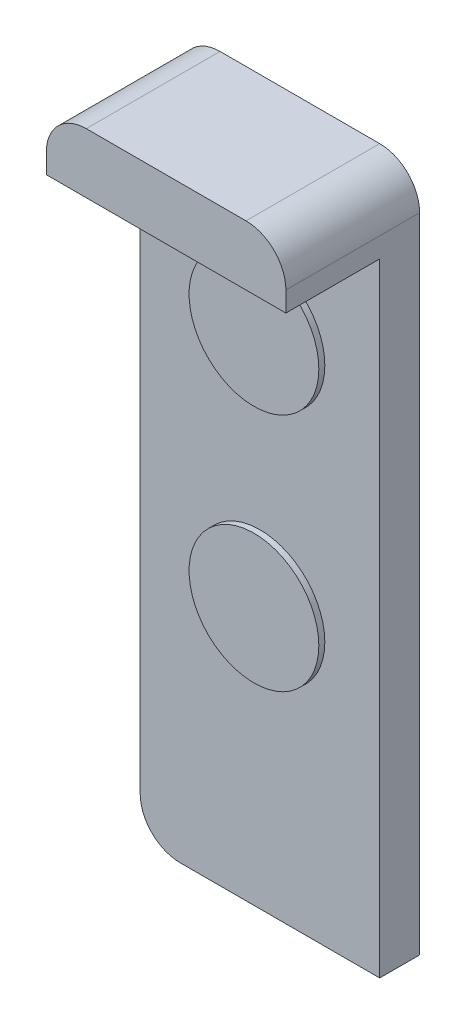
SolidWorks part; units mm, degrees
ref_plane "Plan de face" through (0, 0, 0) normal (0, 0, 1) x (1, 0, 0)
ref_plane "Plan de dessus" through (0, 0, 0) normal (0, 1, 0) x (1, 0, 0)
ref_plane "Plan de droite" through (0, 0, 0) normal (1, 0, 0) x (0, 0, -1)
sketch "Esquisse1" plane through (0, 0, 0) normal (0, 0, 1) x (1, 0, 0)
  line L1 (-3.7662, 20.3915) -> (8.2338, 20.3915)
  line L2 (-3.7662, 20.3915) -> (-3.7662, -13.8085)
  line L3 (-3.7662, -13.8085) -> (8.2338, -13.8085)
  line L4 (8.2338, 20.3915) -> (8.2338, -13.8085)
  point P4 (8.2338, -13.8085)
  dimension "D1" = 34.2
  dimension "D2" = 12
extrude "Boss.-Extru.1" add sketch "Esquisse1" along normal blind 2
sketch "Esquisse2" plane through (0, 0, 2) normal (0, 0, 1) x (1, 0, 0)
  line L0 (8.2338, 20.3915) -> (-3.7662, 20.3915) construction
  circle A0 centre (2.2338, 11.3915) radius 3.25
  circle A1 centre (2.2338, -0.6085) radius 3.25
  point P4 (0, 0)
  point P7 (2.2338, 20.3915)
  dimension "D1" = 6.5
  dimension "D2" = 9
  dimension "D3" = 21
extrude "Boss.-Extru.2" add sketch "Esquisse2" along normal blind 0.3
sketch "Esquisse3" plane through (0, 0, 2) normal (0, 0, 1) x (1, 0, 0)
  line L0 (8.2338, -13.8085) -> (8.2338, 20.3915) construction
  line L1 (-3.7662, 20.3915) -> (8.2338, 20.3915)
  line L2 (-3.7662, 20.3915) -> (-3.7662, 17.3915)
  line L3 (-3.7662, 17.3915) -> (8.2338, 17.3915)
  line L4 (8.2338, 20.3915) -> (8.2338, 17.3915)
  dimension "D1" = 3
extrude "Boss.-Extru.3" add sketch "Esquisse3" along normal blind 4.7
fillet "Congé1" radius 2 3 edges at (8.2338, 20.3915, 3.35) (-3.7662, 20.3915, 3.35) (-3.7662, -13.8085, 1)
